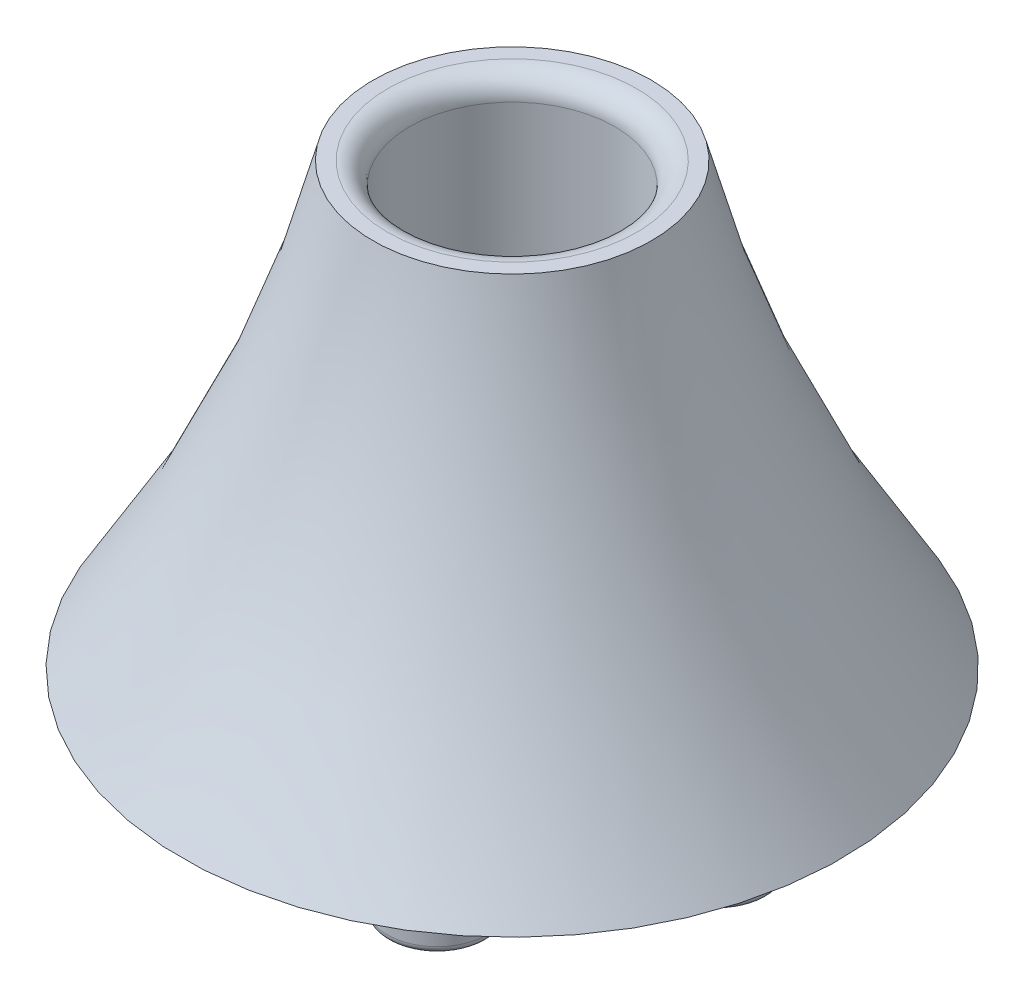
SolidWorks part; units mm, degrees
ref_plane "Front Plane" through (0, 0, 0) normal (0, 0, 1) x (1, 0, 0)
ref_plane "Top Plane" through (0, 0, 0) normal (0, 1, 0) x (1, 0, 0)
ref_plane "Right Plane" through (0, 0, 0) normal (1, 0, 0) x (0, 0, -1)
sketch "Sketch2" plane through (0, 0, 0) normal (1, 0, 0) x (0, 0, -1)
  line L0 (0, 0) -> (0, 9.7295) construction
  line L1 (0, 9.7295) -> (0, -11.8397) construction
  line L2 (0, -11.8397) -> (0, 23.006) construction
  line L3 (0, 0) -> (-7.7721, 0)
  line L4 (-7, 30) -> (-7, 0)
  line L5 (0, 30) -> (-7, 30)
  line L7 (-7, 0) -> (-22.5, 0)
  line L8 (-9.5, 30) -> (-7, 30)
  arc A0 (-9.5, 30) -> (-22.5, 0) centre (-100.8097, 51.7509) cw
  dimension "D1" = 22.5
  dimension "D2" = 30
  dimension "D3" = 7
  dimension "D4" = 2.5
revolve "Revolve1" add sketch "Sketch2" angle 360 about L0
sketch "Sketch3" plane through (0, 0, 0) normal (0, -1, 0) x (-1, 0, 0)
  circle A0 centre (0, 0) radius 14
  circle A1 centre (-14, 0) radius 3.4
  circle A2 centre (-7, 12.1244) radius 3.4
  circle A3 centre (7, 12.1244) radius 3.4
  circle A4 centre (14, 0) radius 3.4
  circle A5 centre (7, -12.1244) radius 3.4
  circle A6 centre (-7, -12.1244) radius 3.4
  point P18 (0, 0)
  dimension "D1" = 28
  dimension "D2" = 6.8
  dimension "D3" = 6
extrude "Boss-Extrude1" add sketch "Sketch3" along normal blind 5 contours A0 A1 | A0 A1 | A0 A6 | A0 A6 | A0 A5 | A0 A5 | A0 A4 | A0 A4 | A0 A3 | A0 A3 | A0 A2 | A0 A2
fillet "Fillet1" radius 1.5 1 edges at (0, 30, -7)
fillet "Fillet2" radius 1.5 1 edges at (0, 0, -7)
fillet "Fillet3" radius 0.5 6 edges at (-14, -5, -3.4) (-7, -5, 8.7244) (7, -5, 8.7244) (14, -5, -3.4) (7, -5, -15.5244) (-7, -5, -15.5244)
